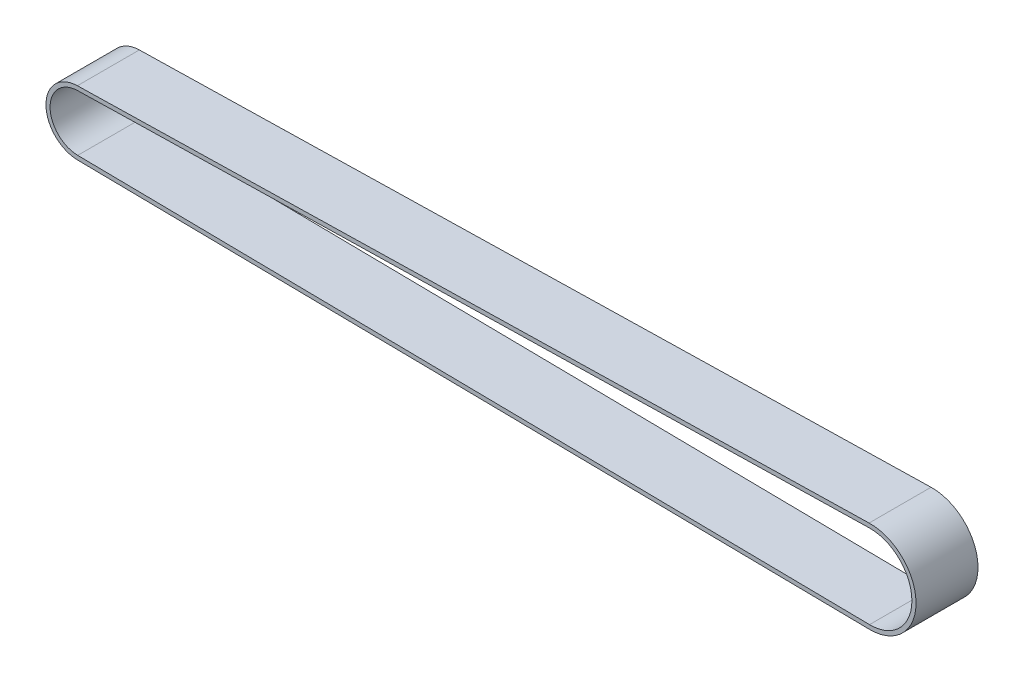
SolidWorks part; units mm, degrees
ref_plane "Front Plane" through (0, 0, 0) normal (0, 0, 1) x (1, 0, 0)
ref_plane "Top Plane" through (0, 0, 0) normal (0, 1, 0) x (1, 0, 0)
ref_plane "Right Plane" through (0, 0, 0) normal (1, 0, 0) x (0, 0, -1)
sketch "Sketch2" plane through (0, 0, 0) normal (0, 0, 1) x (1, 0, 0)
  line L0 (0, 0) -> (1, 0) construction
  line L1 (0, 0) -> (0, 1) construction
  line L2 (-0.1466, 6.7784) -> (191.4918, 10.9231)
  line L3 (191.5764, -9.3236) -> (-0.09, -6.7794)
  arc A0 (-0.09, -6.7794) -> (-0.1466, 6.7784) centre (0, 0) cw
  arc A1 (191.4918, 10.9231) -> (191.5764, -9.3236) centre (191.7108, 0.8005) cw
extrude "Extrude-Thin1" add sketch "Sketch2" along normal mid plane 15 thin thin type one direction wall 1
